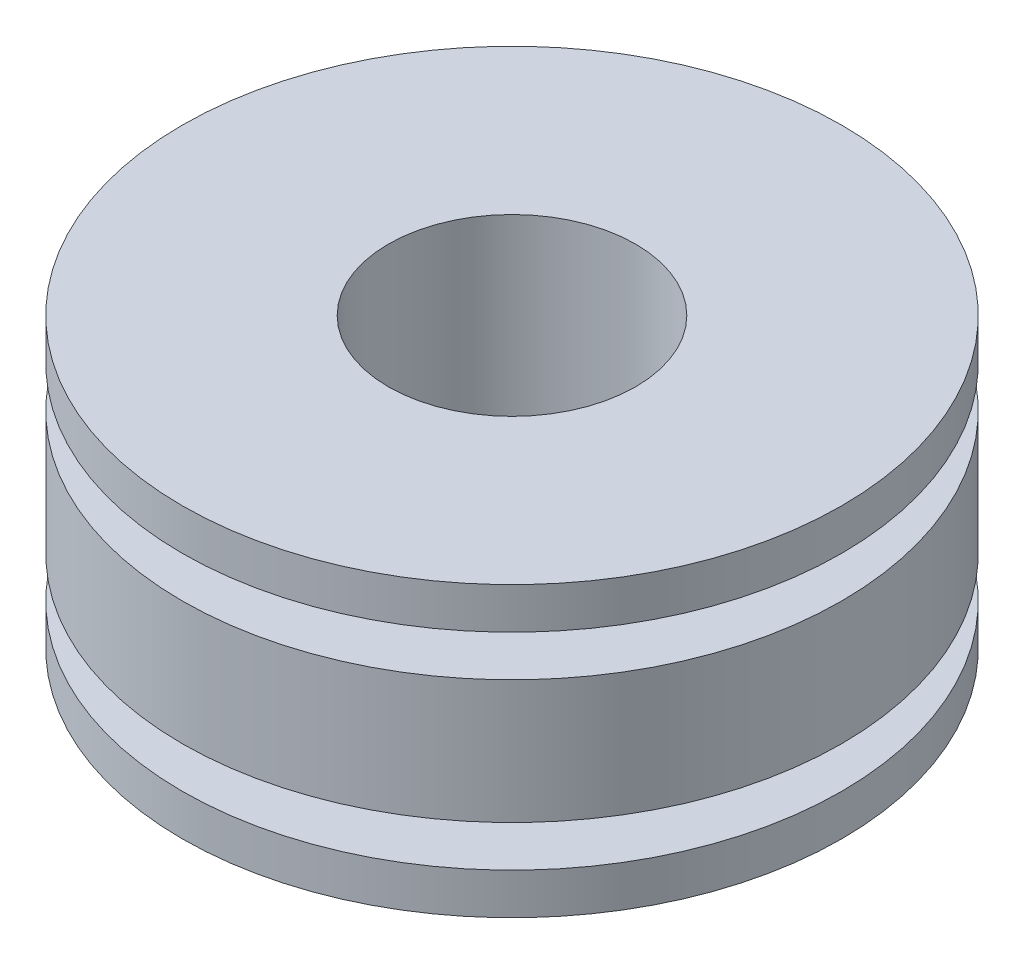
SolidWorks part; units mm, degrees
ref_plane "前视基准面" through (0, 0, 0) normal (0, 0, 1) x (1, 0, 0)
ref_plane "上视基准面" through (0, 0, 0) normal (0, 1, 0) x (1, 0, 0)
ref_plane "右视基准面" through (0, 0, 0) normal (1, 0, 0) x (0, 0, -1)
sketch "草图1" plane through (0, 0, 0) normal (0, 0, 1) x (1, 0, 0)
  line L0 (0, 0) -> (0, 3.5)
  line L1 (0, 3.5) -> (4, 3.5)
  line L2 (4, 3.5) -> (4, 3)
  line L3 (4, 3) -> (3, 3)
  line L4 (3, 3) -> (3, 2.5)
  line L5 (3, 2.5) -> (4, 2.5)
  line L6 (4, 2.5) -> (4, 1)
  line L7 (4, 1) -> (3, 1)
  line L8 (3, 1) -> (3, 0.5)
  line L9 (3, 0.5) -> (4, 0.5)
  line L10 (4, 0.5) -> (4, 0)
  line L11 (4, 0) -> (0, 0)
  line L12 (0, 1.75) -> (4, 1.75) construction
  line L14 (0, 3.5) -> (1.5, 3.5)
  line L15 (0, 3.5) -> (0, 0)
  line L16 (0, 0) -> (1.5, 0)
  line L17 (1.5, 3.5) -> (1.5, 0)
  dimension "D1" = 3.5
  dimension "D2" = 4
  dimension "D3" = 1
  dimension "D4" = 2.5
  dimension "D5" = 1.5
  dimension "D6" = 1.5
revolve "旋转1" add sketch "草图1" angle 360 about L0
